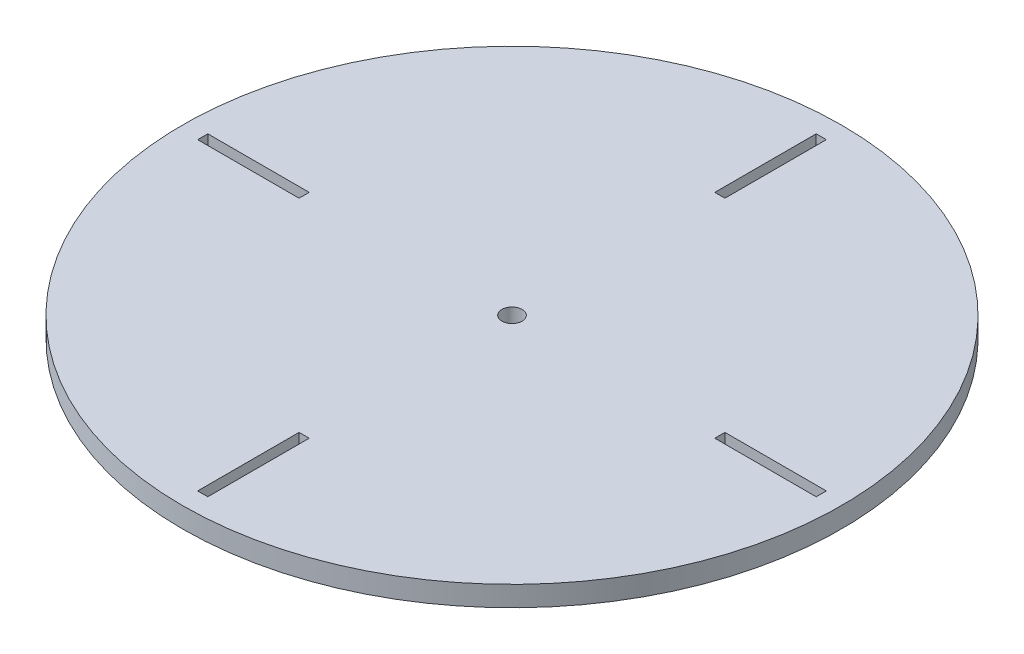
SolidWorks part; units mm, degrees
ref_plane "Front Plane" through (0, 0, 0) normal (0, 0, 1) x (1, 0, 0)
ref_plane "Top Plane" through (0, 0, 0) normal (0, 1, 0) x (1, 0, 0)
ref_plane "Right Plane" through (0, 0, 0) normal (1, 0, 0) x (0, 0, -1)
sketch "Sketch1" plane through (0, 0, 0) normal (0, 1, 0) x (1, 0, 0)
  line L0 (0, 82.55) -> (0, -82.55) construction
  line L1 (-82.55, 0) -> (82.55, 0) construction
  line L2 (77.47, 1.27) -> (77.47, -1.27)
  line L3 (-1.27, 77.47) -> (1.27, 77.47)
  line L4 (-1.27, 77.47) -> (-1.27, 52.07)
  line L5 (-1.27, 52.07) -> (1.27, 52.07)
  line L6 (1.27, 77.47) -> (1.27, 52.07)
  line L7 (-1.27, 77.47) -> (1.27, 52.07) construction
  line L8 (-1.27, 52.07) -> (1.27, 77.47) construction
  line L9 (77.47, 1.27) -> (52.07, 1.27)
  line L10 (52.07, 1.27) -> (52.07, -1.27)
  line L11 (77.47, -1.27) -> (52.07, -1.27)
  line L12 (77.47, 1.27) -> (52.07, -1.27) construction
  line L13 (52.07, 1.27) -> (77.47, -1.27) construction
  line L14 (1.27, -77.47) -> (-1.27, -77.47)
  line L15 (1.27, -77.47) -> (1.27, -52.07)
  line L16 (1.27, -52.07) -> (-1.27, -52.07)
  line L17 (-1.27, -77.47) -> (-1.27, -52.07)
  line L18 (1.27, -77.47) -> (-1.27, -52.07) construction
  line L19 (1.27, -52.07) -> (-1.27, -77.47) construction
  line L20 (-77.47, -1.27) -> (-77.47, 1.27)
  line L21 (-77.47, -1.27) -> (-52.07, -1.27)
  line L22 (-52.07, -1.27) -> (-52.07, 1.27)
  line L23 (-77.47, 1.27) -> (-52.07, 1.27)
  line L24 (-77.47, -1.27) -> (-52.07, 1.27) construction
  line L25 (-52.07, -1.27) -> (-77.47, 1.27) construction
  circle A0 centre (0, 0) radius 82.55
  circle A1 centre (0, 0) radius 2.54
  point P7 (0, 64.77)
  point P15 (64.77, 0)
  point P20 (0, -64.77)
  point P25 (-64.77, 0)
  point P30 (0, 0)
  dimension "D1" = 165.1
  dimension "D6" = 5.08
  dimension "D2" = 5.08
  dimension "D3" = 25.4
  dimension "D4" = 2.54
  dimension "D5" = 4
extrude "Boss-Extrude1" add sketch "Sketch1" along normal blind 5.08
